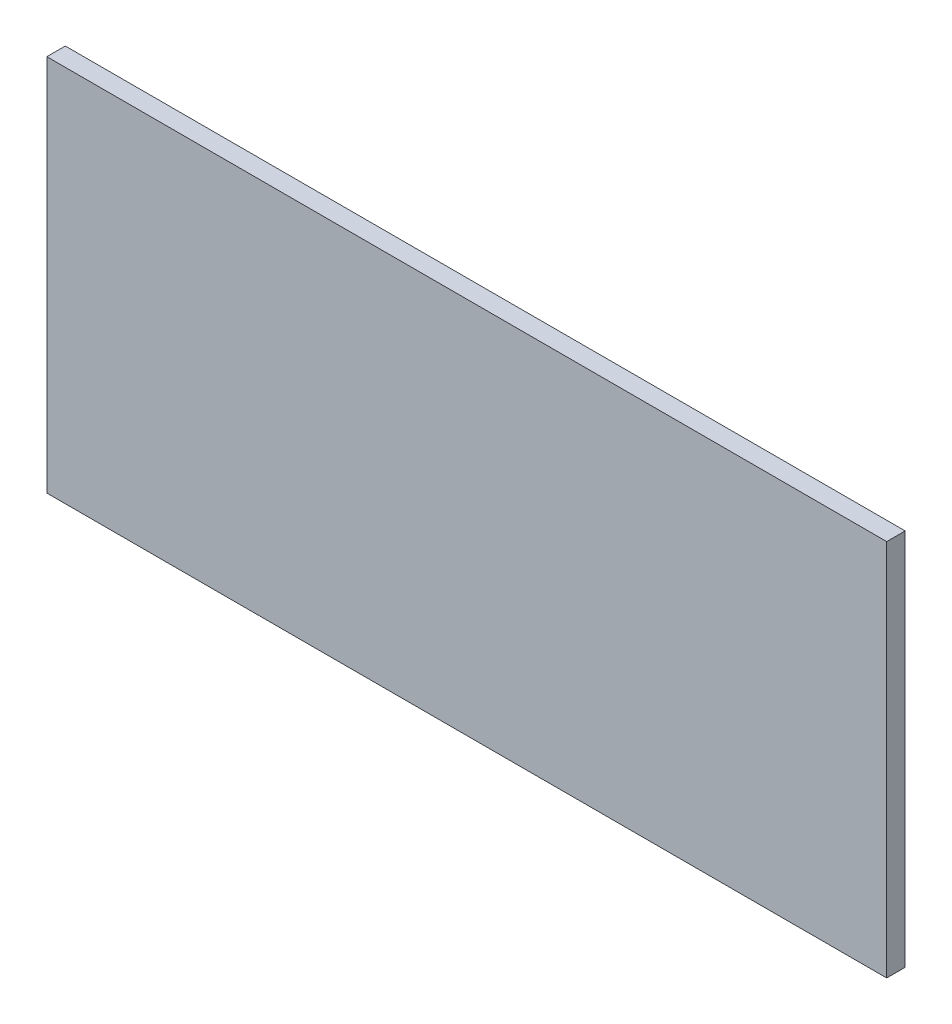
SolidWorks part; units mm, degrees
ref_plane "Front Plane" through (0, 0, 0) normal (0, 0, 1) x (1, 0, 0)
ref_plane "Top Plane" through (0, 0, 0) normal (0, 1, 0) x (1, 0, 0)
ref_plane "Right Plane" through (0, 0, 0) normal (1, 0, 0) x (0, 0, -1)
other "STL Graphics1"
sketch "Sketch1" plane through (0, 0, 0) normal (0, 0, 1) x (1, 0, 0)
  line L4 (47918.0876, 15857.3079) -> (-32081.9124, 15857.3079)
  line L6 (47918.0876, 15857.3079) -> (47918.0876, -20142.6921)
  line L7 (47918.0876, -20142.6921) -> (-32081.9124, -20142.6921)
  line L8 (-32081.9124, 15857.3079) -> (-32081.9124, -20142.6921)
extrude "Boss-Extrude1" add sketch "Sketch1" against normal blind 1760 from offset 3880
